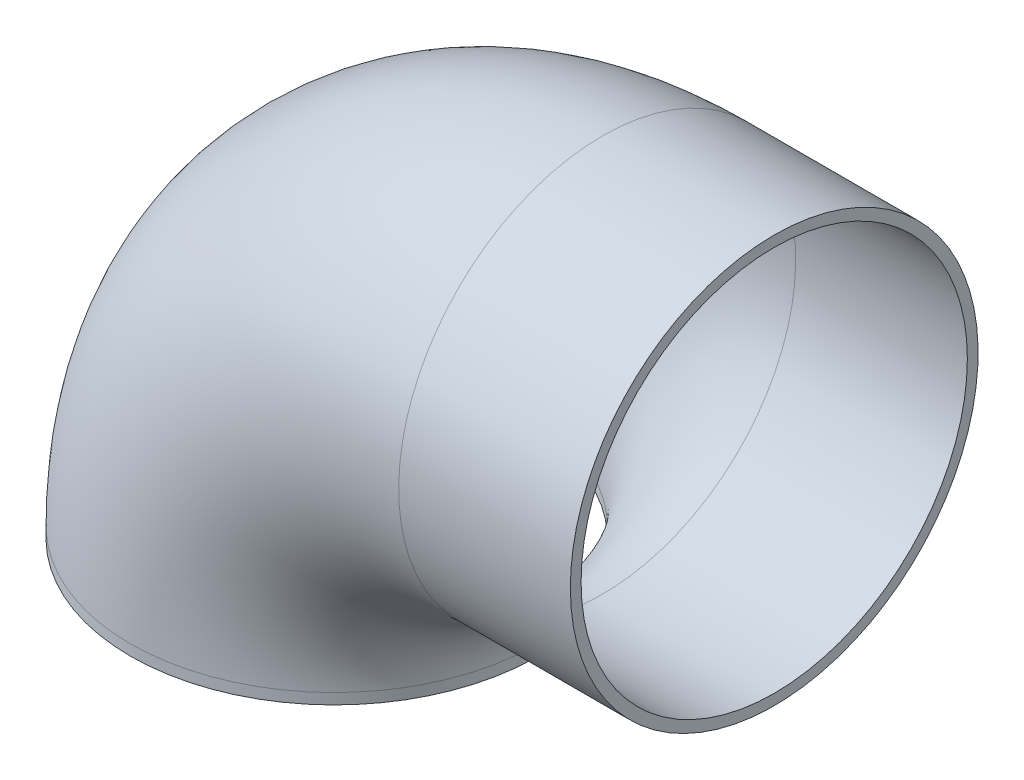
SolidWorks part; units mm, degrees
ref_plane "Front Plane" through (0, 0, 0) normal (0, 0, 1) x (1, 0, 0)
ref_plane "Top Plane" through (0, 0, 0) normal (0, 1, 0) x (1, 0, 0)
ref_plane "Right Plane" through (0, 0, 0) normal (1, 0, 0) x (0, 0, -1)
sketch "Sketch1" plane through (0, 0, 0) normal (0, 0, 1) x (1, 0, 0)
  line L0 (0, 0) -> (0, 2)
  line L1 (50, 52) -> (82, 52)
  arc A0 (0, 2) -> (50, 52) centre (50, 2) cw
  point P6 (0, 52)
  dimension "D3" = 50
  dimension "D1" = 82
  dimension "D2" = 52
sketch "Sketch2" plane through (0, 0, 0) normal (0, 1, 0) x (1, 0, 0)
  circle A0 centre (0, 0) radius 38
  circle A1 centre (0, 0) radius 36
  dimension "D1" = 76
  dimension "D2" = 2
sweep "Sweep1" add profiles "Sketch2" path "Sketch1"
